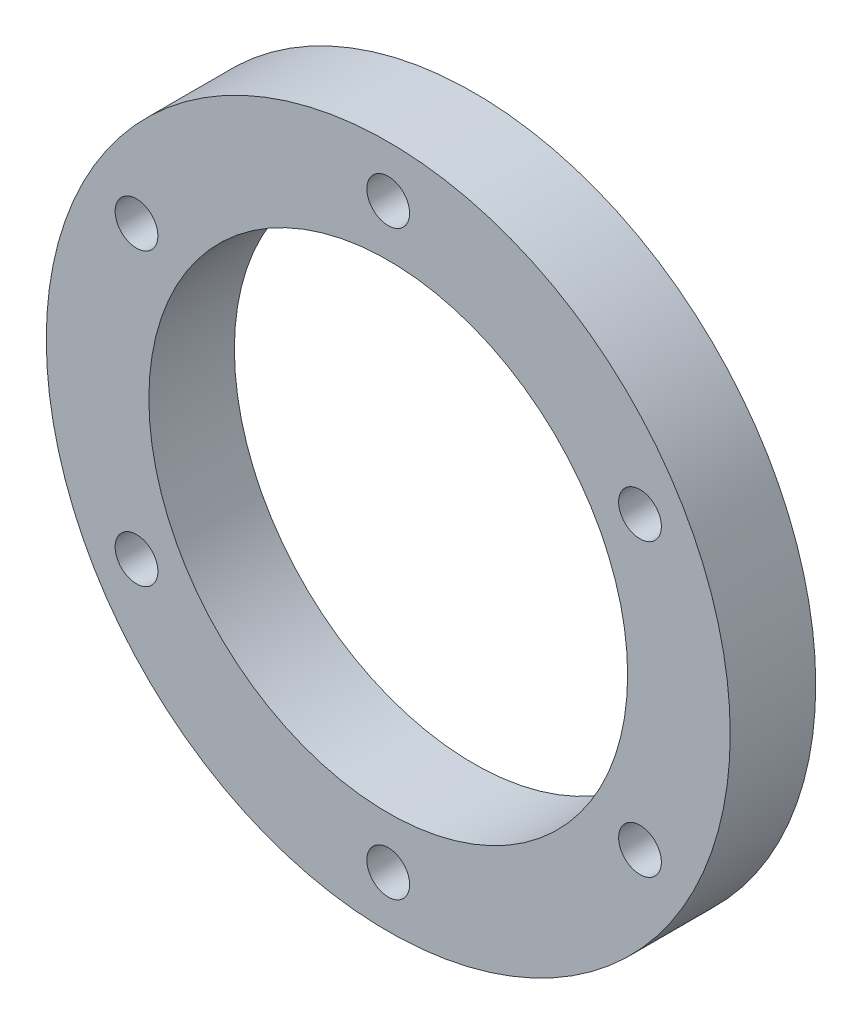
SolidWorks part; units mm, degrees
ref_plane "Front Plane" through (0, 0, 0) normal (0, 0, 1) x (1, 0, 0)
ref_plane "Top Plane" through (0, 0, 0) normal (0, 1, 0) x (1, 0, 0)
ref_plane "Right Plane" through (0, 0, 0) normal (1, 0, 0) x (0, 0, -1)
sketch "Sketch1" plane through (0, 0, 0) normal (0, 0, 1) x (1, 0, 0)
  line L0 (0, 0) -> (0, 17) construction
  circle A0 centre (0, 0) radius 20
  circle A1 centre (0, 0) radius 17 construction
  circle A2 centre (0, 17) radius 1.25
  circle A3 centre (14.7224, 8.5) radius 1.25
  circle A4 centre (14.7224, -8.5) radius 1.25
  circle A5 centre (0, -17) radius 1.25
  circle A6 centre (-14.7224, -8.5) radius 1.25
  circle A7 centre (-14.7224, 8.5) radius 1.25
  circle A8 centre (0, 0) radius 14
  point P19 (0, 0)
  dimension "D1" = 34
  dimension "D2" = 40
  dimension "D3" = 2.5
  dimension "D5" = 28
  dimension "D4" = 6
extrude "Boss-Extrude1" add sketch "Sketch1" along normal blind 5
